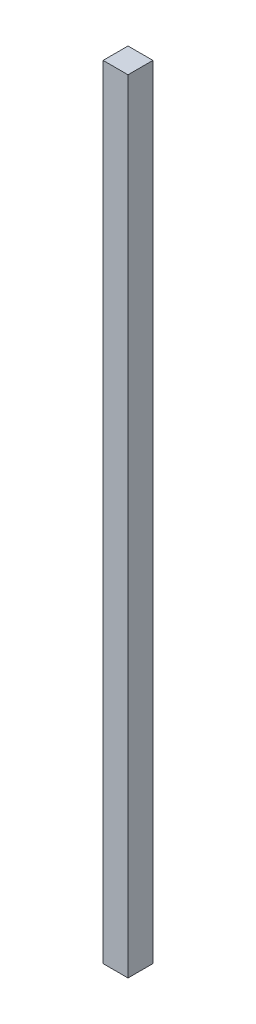
SolidWorks part; units mm, degrees
ref_plane "Front Plane" through (0, 0, 0) normal (0, 0, 1) x (1, 0, 0)
ref_plane "Top Plane" through (0, 0, 0) normal (0, 1, 0) x (1, 0, 0)
ref_plane "Right Plane" through (0, 0, 0) normal (1, 0, 0) x (0, 0, -1)
sketch "Sketch1" plane through (0, 0, 0) normal (0, 1, 0) x (1, 0, 0)
  line L1 (-5.9447, 14.7266) -> (19.4553, 14.7266)
  line L2 (-5.9447, 14.7266) -> (-5.9447, -10.6734)
  line L3 (-5.9447, -10.6734) -> (19.4553, -10.6734)
  line L4 (19.4553, 14.7266) -> (19.4553, -10.6734)
  dimension "D1" = 25.4
  dimension "D2" = 25.4
extrude "Boss-Extrude1" add sketch "Sketch1" along normal blind 797.56
